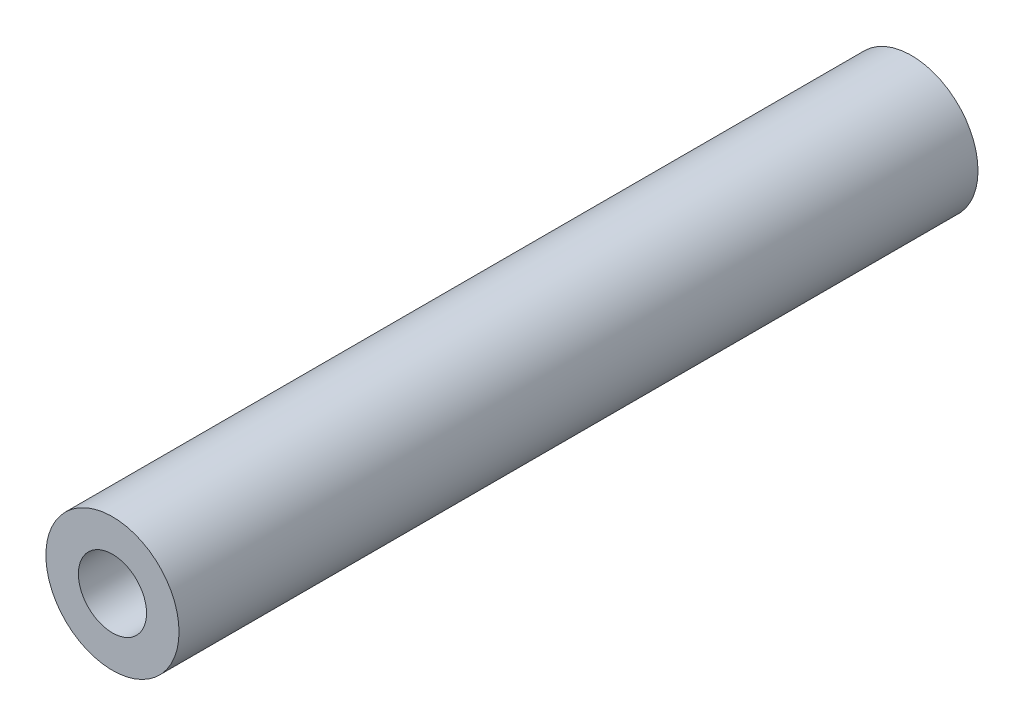
SolidWorks part; units mm, degrees
ref_plane "Front Plane" through (0, 0, 0) normal (0, 0, 1) x (1, 0, 0)
ref_plane "Top Plane" through (0, 0, 0) normal (0, 1, 0) x (1, 0, 0)
ref_plane "Right Plane" through (0, 0, 0) normal (1, 0, 0) x (0, 0, -1)
sketch "Sketch1" plane through (0, 0, 0) normal (0, 0, 1) x (1, 0, 0)
  circle A0 centre (0, 0) radius 4.7625
  circle A1 centre (0, 0) radius 2.4384
  dimension "OD" = 9.525
  dimension "ID" = 4.8768
extrude "Extrude1" add sketch "Sketch1" along normal mid plane 57.15
sketch "Sketch2" plane through (0, 0, 0) normal (1, 0, 0) x (0, 0, -1)
  line L0 (-28.575, -2.4384) -> (28.575, -2.4384) construction
  line L3 (28.575, 2.4384) -> (-28.575, 2.4384) construction
  line L5 (-28.575, -2.4384) -> (28.575, -2.4384)
  line L6 (28.575, 2.4384) -> (-28.575, 2.4384)
sketch "Sketch4" plane through (0, 0, 28.575) normal (0, 0, 1) x (1, 0, 0)
  line L0 (0, 0) -> (-1.7242, 1.7242)
  line L1 (0, -2.1828) -> (0, 2.1828) construction
  circle A0 centre (0, 0) radius 2.4384 construction
  dimension "D1" = 45
